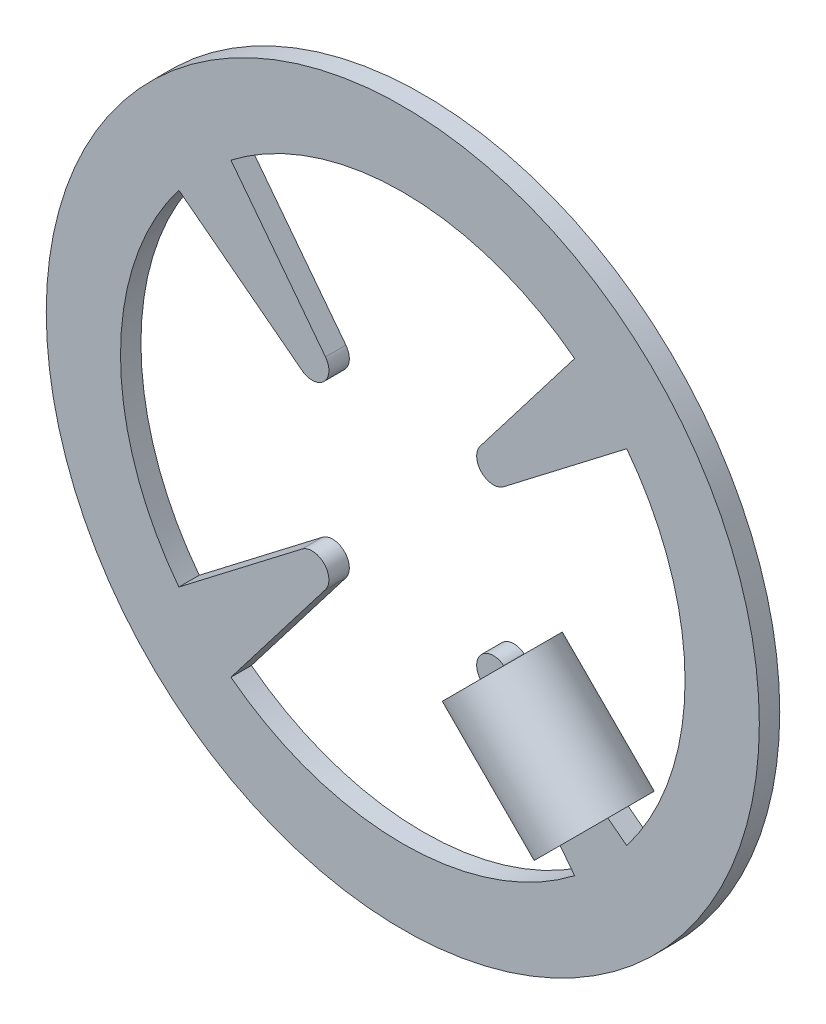
SolidWorks part; units mm, degrees
other "標示1"
sketch "草圖65"
ref_plane "前基準面" through (0, 0, 0) normal (0, 0, 1) x (1, 0, 0)
ref_plane "上基準面" through (0, 0, 0) normal (0, 1, 0) x (1, 0, 0)
ref_plane "右基準面" through (0, 0, 0) normal (1, 0, 0) x (0, 0, -1)
sketch "草圖1" plane through (0, 0, 0) normal (0, 0, 1) x (1, 0, 0)
  circle A0 centre (0, 0) radius 0.96
  circle A1 centre (0, 0) radius 0.76
extrude "填料-伸長1" add sketch "草圖1" along normal blind 0.055
sketch "草圖2" plane through (0, 0, 0.055) normal (0, 0, 1) x (1, 0, 0)
  line L0 (0, 0) -> (0, 1.565) construction
  line L1 (0, 0) -> (-1.8584, 0) construction
  line L2 (-0.0447, 0.3392) -> (-0.0992, 0.7535)
  line L3 (0.0447, 0.3392) -> (0.0992, 0.7535)
  line L4 (0.2714, 0.2082) -> (0.6029, 0.4627)
  line L5 (0.2082, 0.2714) -> (0.4627, 0.6029)
  line L6 (0.2082, -0.2714) -> (0.4627, -0.6029)
  line L7 (0.2714, -0.2082) -> (0.6029, -0.4627)
  line L8 (-0.2714, -0.2082) -> (-0.6029, -0.4627)
  line L9 (-0.2082, -0.2714) -> (-0.4627, -0.6029)
  line L10 (-0.2082, 0.2714) -> (-0.4627, 0.6029)
  line L11 (-0.2714, 0.2082) -> (-0.6029, 0.4627)
  circle A0 centre (0, 0) radius 0.3
  circle A1 centre (0, 0) radius 0.76 construction
  arc A3 (-0.0447, 0.3392) -> (0.0447, 0.3392) centre (0, 0.345) ccw
  arc A4 (0.0992, 0.7535) -> (-0.0992, 0.7535) centre (0, 0) ccw
  arc A5 (-0.76, 0) -> (0.76, 0) centre (0, 0) ccw
  arc A6 (0.6029, 0.4627) -> (0.4627, 0.6029) centre (0, 0) ccw
  arc A7 (0.2082, 0.2714) -> (0.2714, 0.2082) centre (0.244, 0.244) ccw
  arc A8 (0.4627, -0.6029) -> (0.6029, -0.4627) centre (0, 0) ccw
  arc A9 (0.2714, -0.2082) -> (0.2082, -0.2714) centre (0.244, -0.244) ccw
  arc A10 (-0.6029, -0.4627) -> (-0.4627, -0.6029) centre (0, 0) ccw
  arc A11 (-0.2082, -0.2714) -> (-0.2714, -0.2082) centre (-0.244, -0.244) ccw
  arc A12 (-0.4627, 0.6029) -> (-0.6029, 0.4627) centre (0, 0) ccw
  arc A13 (-0.2714, 0.2082) -> (-0.2082, 0.2714) centre (-0.244, 0.244) ccw
  point P23 (0, 0)
  point P34 (0, 0)
  point P41 (0, 0)
  circle M4 centre (0, 0) radius 0.76
  dimension "D1" = 7.5
  dimension "D3" = 2
  dimension "D4" = 4
  dimension "D2" = 7.5
extrude "填料-伸長2" add sketch "草圖2" against normal blind 0.055 contours L11 A13 L10 M4 | L5 A7 L4 M4 | L7 A9 L6 M4 | A11 L8 L9 M4
sketch "草圖7" plane through (0, 0, 0.055) normal (0, 0, 1) x (1, 0, 0)
  line L0 (0.2121, 0.2121) -> (0.2404, 0.2404) construction
  line L1 (0.2404, 0.2404) -> (0.2013, 0.2795) construction
  line L2 (0.2404, 0.2404) -> (0.5894, 0.5894) construction
  line L3 (0.0244, -0.0244) -> (-0.6648, 0.6648) construction
  line L4 (0.2404, -0.2404) -> (0.3328, -0.148)
  arc A0 (0.2082, 0.2714) -> (0.2714, 0.2082) centre (0.244, 0.244) ccw construction
  arc A1 (-0.2082, -0.2714) -> (-0.2714, -0.2082) centre (-0.244, -0.244) ccw construction
  arc A2 (-0.2714, 0.2082) -> (-0.2082, 0.2714) centre (-0.244, 0.244) ccw construction
  arc A3 (0.2714, -0.2082) -> (0.2082, -0.2714) centre (0.244, -0.244) ccw construction
  point P5 (0.297, 0.297)
  point P7 (-0.2121, -0.2121)
  point P8 (0.3536, 0.3536)
  point P9 (0.4101, 0.4101)
  point P12 (-0.2404, -0.2404)
  point P16 (-0.297, -0.297)
  point P17 (-0.3536, -0.3536)
  point P18 (-0.4101, -0.4101)
  point P20 (0.2404, -0.2404)
  point P23 (-0.2404, 0.2404)
  point P24 (-0.2121, 0.2121)
  point P25 (0.2121, -0.2121)
  point P29 (0.297, -0.297)
  point P33 (0.3536, -0.3536)
  point P34 (0.4101, -0.4101)
  point P35 (-0.297, 0.297)
  point P36 (-0.3536, 0.3536)
  point P37 (-0.4101, 0.4101)
  point P40 (0.4667, -0.4667)
  point P41 (0.5233, -0.5233)
  point P42 (0.4667, 0.4667)
  point P43 (0.5233, 0.5233)
  point P44 (-0.4667, 0.4667)
  point P45 (-0.5233, 0.5233)
  point P46 (-0.4667, -0.4667)
  point P47 (-0.5233, -0.5233)
  dimension "D1" = 0.08
  dimension "D2" = 0.08
  dimension "D3" = 0.08
  dimension "D4" = 0.04
  dimension "D5" = 0.04
  dimension "D6" = 0.08
  dimension "D7" = 0.08
  dimension "D8" = 0.08
  dimension "D9" = 0.04
  dimension "D10" = 0.04
  dimension "D11" = 0.08
  dimension "D12" = 0.08
  dimension "D13" = 0.08
  dimension "D14" = 0.08
  dimension "D15" = 0.08
  dimension "D16" = 0.08
  dimension "D17" = 0.08
  dimension "D18" = 0.08
  dimension "D19" = 0.08
  dimension "D20" = 0.08
  dimension "D21" = 0.08
  dimension "D22" = 0.08
  dimension "D23" = 0.08
  dimension "D24" = 0.08
ref_plane "平面5" through (0.2404, 0.2404, 0) normal (0.7071, 0.7071, 0) x (-0.7071, 0.7071, 0)
ref_plane "平面6" through (0.297, 0.297, 0) normal (0.7071, 0.7071, 0) x (0.7071, -0.7071, 0)
ref_plane "平面7" through (0.3536, 0.3536, 0) normal (0.7071, 0.7071, 0) x (0.7071, -0.7071, 0)
ref_plane "平面8" through (0.4101, 0.4101, 0) normal (0.7071, 0.7071, 0) x (0.7071, -0.7071, 0)
ref_plane "平面9" through (-0.2404, -0.2404, 0) normal (0.7071, 0.7071, 0) x (0.7071, -0.7071, 0)
ref_plane "平面10" through (-0.297, -0.297, 0) normal (0.7071, 0.7071, 0) x (0.7071, -0.7071, 0)
ref_plane "平面11" through (-0.3536, -0.3536, 0) normal (0.7071, 0.7071, 0) x (0.7071, -0.7071, 0)
ref_plane "平面12" through (-0.4101, -0.4101, 0) normal (0.7071, 0.7071, 0) x (0.7071, -0.7071, 0)
ref_plane "平面13" through (0.2404, -0.2404, 0) normal (0.7071, -0.7071, 0) x (0.7071, 0.7071, 0)
ref_plane "平面14" through (0.297, -0.297, 0) normal (0.7071, -0.7071, 0) x (0, 0, -1)
ref_plane "平面15" through (0.3536, -0.3536, 0) normal (0.7071, -0.7071, 0) x (0, 0, -1)
ref_plane "平面16" through (0.4101, -0.4101, 0) normal (0.7071, -0.7071, 0) x (0, 0, -1)
ref_plane "平面17" through (-0.2404, 0.2404, 0) normal (0.7071, -0.7071, 0) x (0, 0, -1)
ref_plane "平面18" through (-0.297, 0.297, 0) normal (0.7071, -0.7071, 0) x (0, 0, -1)
ref_plane "平面19" through (-0.3536, 0.3536, 0) normal (0.7071, -0.7071, 0) x (0, 0, -1)
ref_plane "平面20" through (-0.4101, 0.4101, 0) normal (0.7071, -0.7071, 0) x (0, 0, -1)
sketch "草圖66" plane through (0.2404, -0.2404, 0) normal (0.7071, -0.7071, 0) x (0.7071, 0.7071, 0)
  line L0 (0, 0.055) -> (0, 0.2) construction
  circle A0 centre (0, 0.0275) radius 0.1
  circle A1 centre (0, 0.0275) radius 0.132
  point P1 (0, 0.0275)
  dimension "D1" = 0.0275
extrude "填料-伸長3" add sketch "草圖66" along normal blind 0.35 separate body
